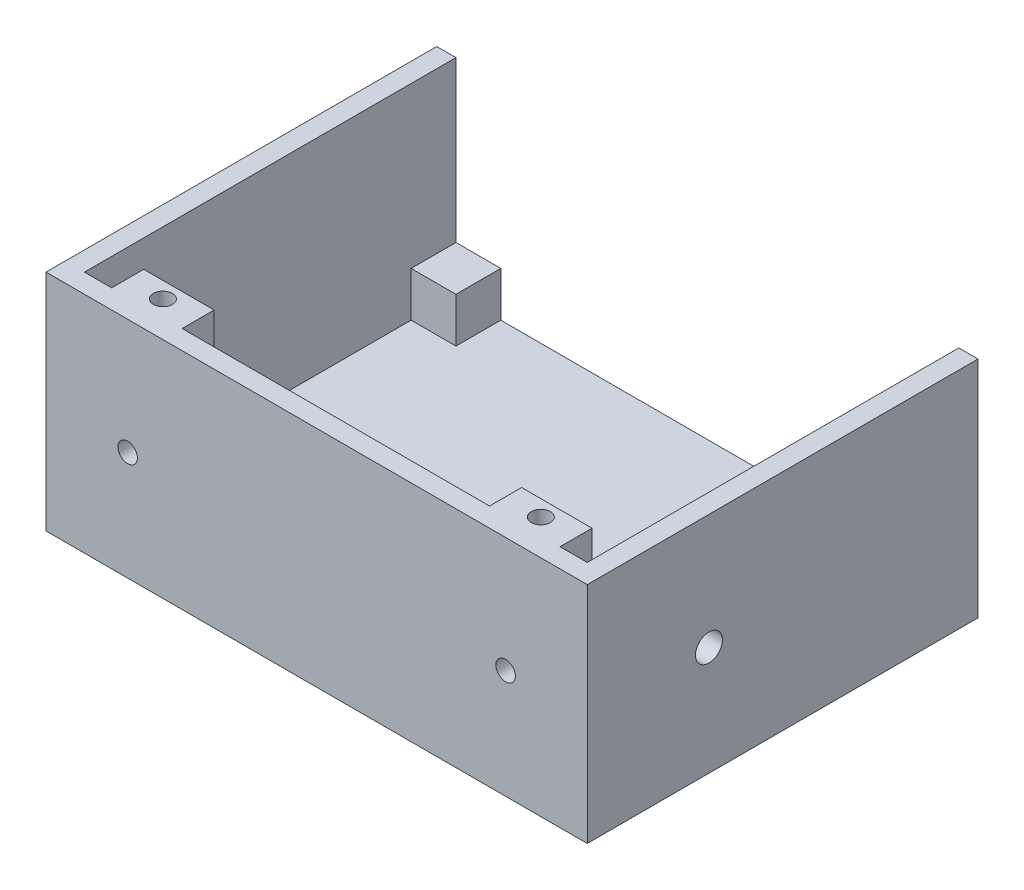
SolidWorks part; units mm, degrees
ref_plane "前视基准面" through (0, 0, 0) normal (0, 0, 1) x (1, 0, 0)
ref_plane "上视基准面" through (0, 0, 0) normal (0, 1, 0) x (1, 0, 0)
ref_plane "右视基准面" through (0, 0, 0) normal (1, 0, 0) x (0, 0, -1)
other "Configuration Table"
sketch "草图1" plane through (0, 0, 0) normal (0, 0, 1) x (1, 0, 0)
  line L0 (0, 0) -> (42.25, 0)
  line L1 (0, 0) -> (-42.25, 0)
  line L6 (0, 35) -> (-42.25, 35)
  line L8 (0, 35) -> (42.25, 35)
  line L9 (42.25, 35) -> (42.25, 0)
  line L10 (-42.25, 35) -> (-42.25, 0)
  circle A0 centre (-29.5, 17) radius 1.52
  circle A1 centre (29.5, 17) radius 1.52
extrude "凸台-拉伸2" add sketch "草图1" along normal blind 3 contours A0 | L0 L9 L8 L6 L10 L1 | A1
sketch "草图2" plane through (0, 0, 0) normal (0, 0, -1) x (-1, 0, 0)
  line L0 (42.25, 35) -> (42.25, 0) construction
  line L1 (-42.25, 0) -> (42.25, 0)
  line L2 (-42.25, 0) -> (-42.25, 3)
  line L3 (-42.25, 3) -> (42.25, 3)
  line L4 (42.25, 0) -> (42.25, 3)
extrude "凸台-拉伸3" add sketch "草图2" along normal blind 58 contours L2 L1 L4 L3
sketch "草图3" plane through (0, 0, 0) normal (0, 0, -1) x (-1, 0, 0)
  line L0 (-42.25, 3) -> (42.25, 3) construction
  line L1 (-42.25, 35) -> (-39.25, 35)
  line L2 (-42.25, 35) -> (-42.25, 3)
  line L3 (-42.25, 3) -> (-39.25, 3)
  line L4 (-39.25, 35) -> (-39.25, 3)
  line L6 (42.25, 35) -> (39.25, 35)
  line L7 (42.25, 35) -> (42.25, 3)
  line L8 (42.25, 3) -> (39.25, 3)
  line L9 (39.25, 35) -> (39.25, 3)
  line M10 (-42.25, 3) -> (42.25, 3)
  line M11 (42.25, 3) -> (42.25, 35)
  line M12 (42.25, 35) -> (-42.25, 35)
extrude "凸台-拉伸4" add sketch "草图3" along normal blind 58 contours L9 M12 M10 M11 | L2 L1 L4 L3
sketch "草图5" plane through (42.25, 0, 0) normal (1, 0, 0) x (0, 0, -1)
  line L0 (-3, 0) -> (-3, 17)
  line L1 (-3, 35) -> (-3, 0) construction
  line L2 (-3, 17) -> (16, 17)
  circle A0 centre (16, 17) radius 2.1
extrude "切除-拉伸1" cut sketch "草图5" against normal blind 58
sketch "草图12" plane through (0, 0, 0) normal (0, 0, -1) x (-1, 0, 0)
  line L0 (-35, 35) -> (-24, 35)
  line L1 (-29.5, 28) -> (-24, 28)
  line L2 (24, 35) -> (35, 35)
  line L3 (-24, 28) -> (-24, 35)
  line L4 (-29.5, 28) -> (-35, 28)
  line L5 (-35, 28) -> (-35, 35)
  line L7 (29.5, 28) -> (35, 28)
  line L8 (29.5, 28) -> (24, 28)
  line L9 (24, 35) -> (24, 28)
  line L10 (35, 35) -> (35, 28)
extrude "凸台-拉伸9" add sketch "草图12" along normal blind 5 contours L5 L4 L1 L3 L0 | L8 L9 L2 L10 L7
sketch "草图14" plane through (0, 35, 0) normal (0, 1, 0) x (1, 0, 0)
  line L0 (-35, 5) -> (-24, 0)
  line L1 (24, 5) -> (35, 0)
  circle A0 centre (-29.5, 2.5) radius 1.49
  circle A1 centre (29.5, 2.5) radius 1.49
extrude "切除-拉伸4" cut sketch "草图14" against normal blind 4 contours L0 A0 | L0 A0 | L1 A1 | L1 A1
sketch "草图15" plane through (0, 3, 0) normal (0, 1, 0) x (1, 0, 0)
  line L1 (-39.25, 58) -> (-32.25, 58)
  line L2 (-39.25, 58) -> (-39.25, 51)
  line L3 (-39.25, 51) -> (-32.25, 51)
  line L4 (-32.25, 58) -> (-32.25, 51)
  line L5 (39.25, 58) -> (32.25, 58)
  line L6 (39.25, 58) -> (39.25, 51)
  line L7 (39.25, 51) -> (32.25, 51)
  line L8 (32.25, 58) -> (32.25, 51)
  line M9 (39.25, 0) -> (39.25, 58)
  line M10 (39.25, 58) -> (-39.25, 58)
extrude "凸台-拉伸10" add sketch "草图15" along normal blind 7 contours L8 L7 M10 M9 | L2 L1 L4 L3
sketch "草图16" plane through (0, 0, -58) normal (0, 0, -1) x (-1, 0, 0)
  line L0 (-39.25, 10) -> (-32.25, 3)
  line L1 (32.25, 3) -> (39.25, 10)
  circle A0 centre (-35.75, 6.5) radius 1.49
  circle A1 centre (35.75, 6.5) radius 1.49
extrude "切除-拉伸5" cut sketch "草图16" against normal blind 5 contours L0 A0 | L0 A0 | L1 A1 | L1 A1
